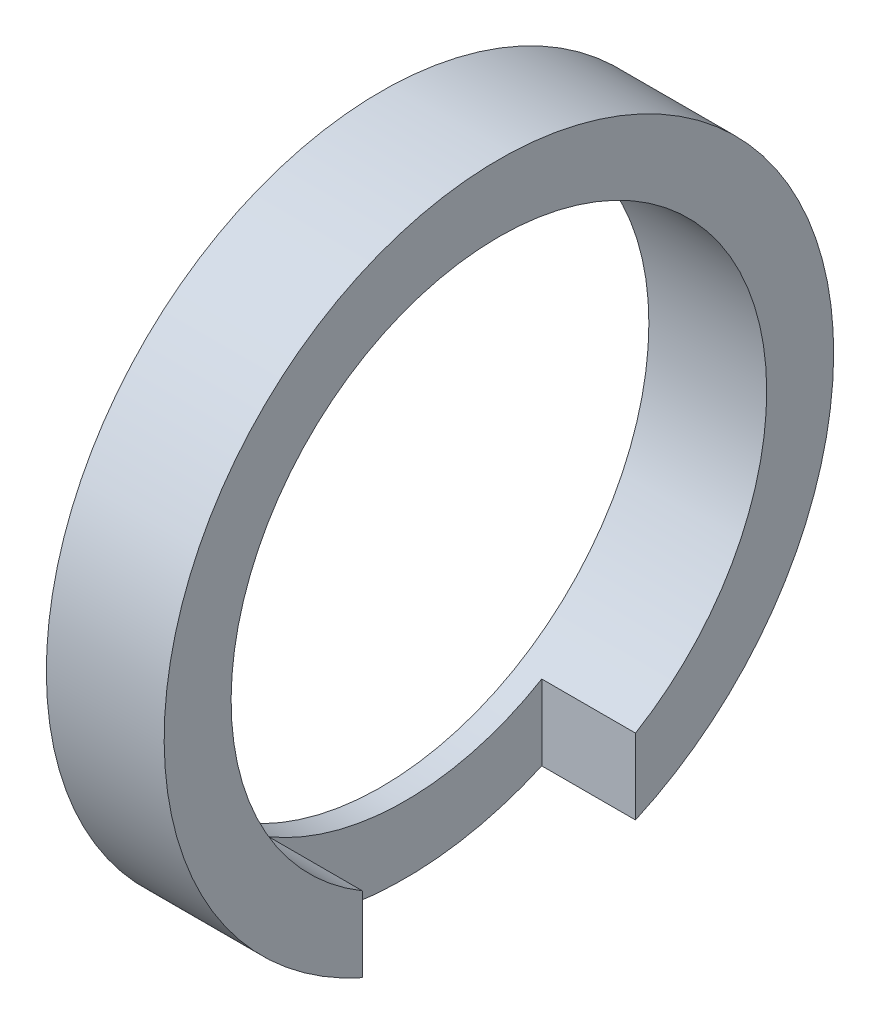
SolidWorks part; units mm, degrees
material "6061-T6 (SS)"
ref_plane "Front Plane" through (0, 0, 0) normal (0, 0, 1) x (1, 0, 0)
ref_plane "Top Plane" through (0, 0, 0) normal (0, 1, 0) x (1, 0, 0)
ref_plane "Right Plane" through (0, 0, 0) normal (1, 0, 0) x (0, 0, -1)
sketch "Sketch1" plane through (0, 0, 0) normal (1, 0, 0) x (0, 0, -1)
  circle A0 centre (0, 0) radius 12.7
  circle A1 centre (0, 0) radius 15.875
  dimension "D1" = 25.4
  dimension "D2" = 31.75
extrude "Boss-Extrude1" add sketch "Sketch1" along normal blind 5.588
sketch "Sketch2" plane through (5.588, 0, 0) normal (1, 0, 0) x (0, 0, -1)
  circle A0 centre (0, 0) radius 14.2875
  circle A1 centre (0, 0) radius 15.875
  dimension "D1" = 28.575
extrude "Cut-Extrude1" [suppressed] cut sketch "Sketch2" against normal through all
sketch "Sketch3" plane through (5.588, 0, 0) normal (1, 0, 0) x (0, 0, -1)
  line L0 (-6.477, -10.9242) -> (-6.477, -14.4936)
  line L1 (6.477, -10.9242) -> (6.477, -14.4936)
  line L2 (-6.477, -10.9242) -> (6.477, -10.9242)
  circle A0 centre (0, 0) radius 15.875 construction
  arc A1 (6.477, -14.4936) -> (-6.477, -14.4936) centre (0, 0) cw
  circle A2 centre (0, 0) radius 12.7 construction
  point P8 (0, 0)
  point P11 (0, 0)
  point P12 (6.1072, -14.6532)
  dimension "D1" = 12.954
extrude "Cut-Extrude2" cut sketch "Sketch3" against normal blind 4.445
